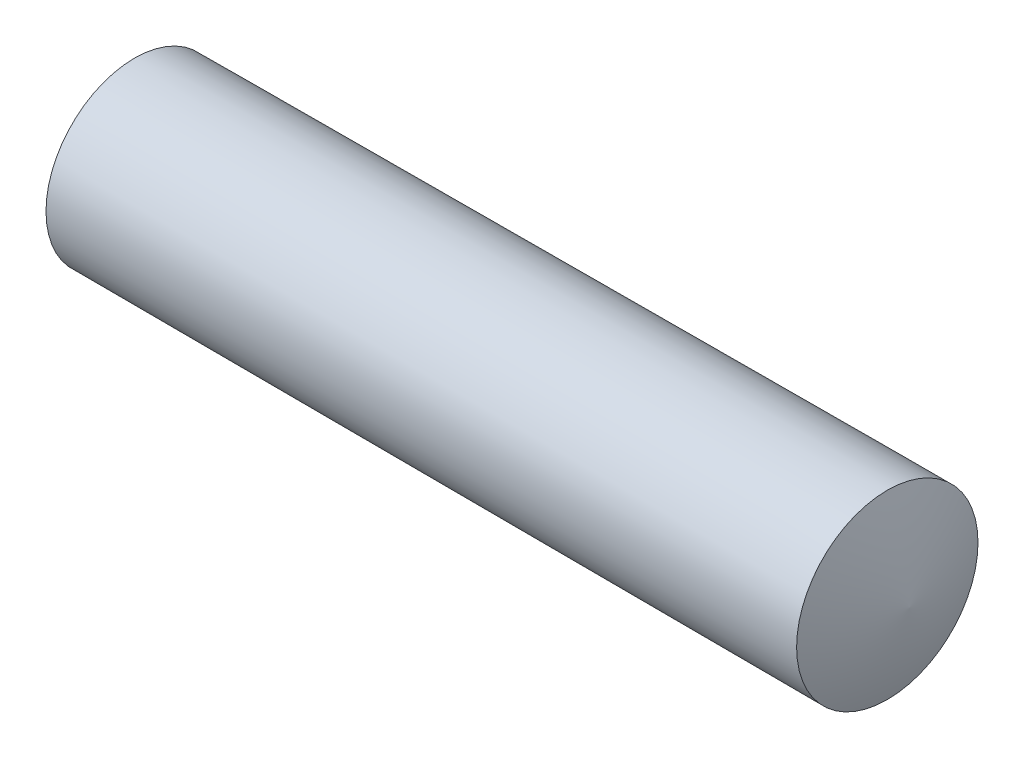
SolidWorks part; units mm, degrees
material "Y12"
ref_plane "前视" through (0, 0, 0) normal (0, 0, 1) x (1, 0, 0)
ref_plane "上视" through (0, 0, 0) normal (0, 1, 0) x (1, 0, 0)
ref_plane "右视" through (0, 0, 0) normal (1, 0, 0) x (0, 0, -1)
sketch "草图1" plane through (0, 0, 0) normal (0, 0, 1) x (1, 0, 0)
  line L0 (-2.32, 2) -> (14.68, 2.0482) construction
  line L1 (-2.82, 0) -> (15.18, 0)
  line L2 (0, 0) -> (1.2454, 0) construction
  line L6 (-2.32, -2) -> (14.68, -2.0482)
  arc A0 (15.18, 0) -> (14.68, -2.0482) centre (6.9493, 0.9241) cw
  arc A1 (-2.82, 0) -> (-2.32, -2) centre (5.1264, 0.9241) ccw
  dimension "r2" = 8.2824
  dimension "r1" = 8
  dimension "D1" = 18
  dimension "a" = 0.5
  dimension "D3" = 0.5
  dimension "D/2" = 4
revolve "基体-旋转" add sketch "草图1" angle 360 about L2
equation "\"r1@草图1\" = \"D/2@草图1\" * 2"
equation "\"D3@草图1\" = \"a@草图1\""
equation "\"r2@草图1\" = \"a@草图1\" / 2 + \"D/2@草图1\" * 2 + (  0.02 * \"D1@草图1\" ) * (  0.02 * \"D1@草图1\" ) / (  8 * \"a@草图1\"  ) "
